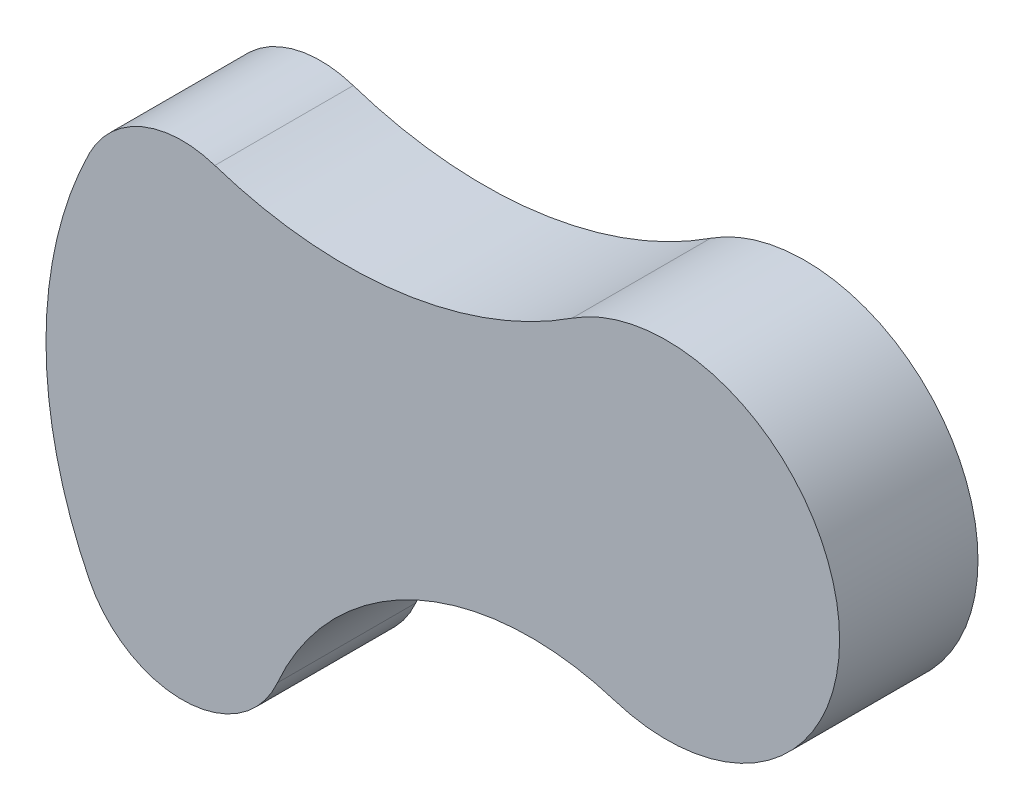
SolidWorks part; units mm, degrees
ref_plane "Alzado" through (0, 0, 0) normal (0, 0, 1) x (1, 0, 0)
ref_plane "Planta" through (0, 0, 0) normal (0, 1, 0) x (1, 0, 0)
ref_plane "Vista lateral" through (0, 0, 0) normal (1, 0, 0) x (0, 0, -1)
sketch "Croquis1" plane through (0, 0, 0) normal (0, 0, 1) x (1, 0, 0)
  arc A0 (-3.7659, -11.9192) -> (-6.8277, 10.4705) centre (0, 0) ccw
  arc A1 (-32.6429, 7.12) -> (-41.7185, 3.3333) centre (-35, 0) ccw
  arc A2 (-41.7185, -23.3333) -> (-28.1249, -22.9973) centre (-35, -20) ccw
  arc A3 (-32.6429, 7.12) -> (-6.8277, 10.4705) centre (-23.2143, 35.5998) ccw
  arc A4 (-28.1249, -22.9973) -> (-3.7659, -11.9192) centre (-9.7915, -30.99) cw
  arc A5 (-41.7185, -23.3333) -> (-41.7185, 3.3333) centre (-14.8444, -10) cw
  dimension "D3" = 7.5
  dimension "D4" = 12.5
  dimension "D5" = 30
  dimension "D6" = 20
  dimension "D7" = 30
  dimension "D1" = 35
  dimension "D2" = 20
extrude "Saliente-Extruir1" add sketch "Croquis1" along normal blind 10
